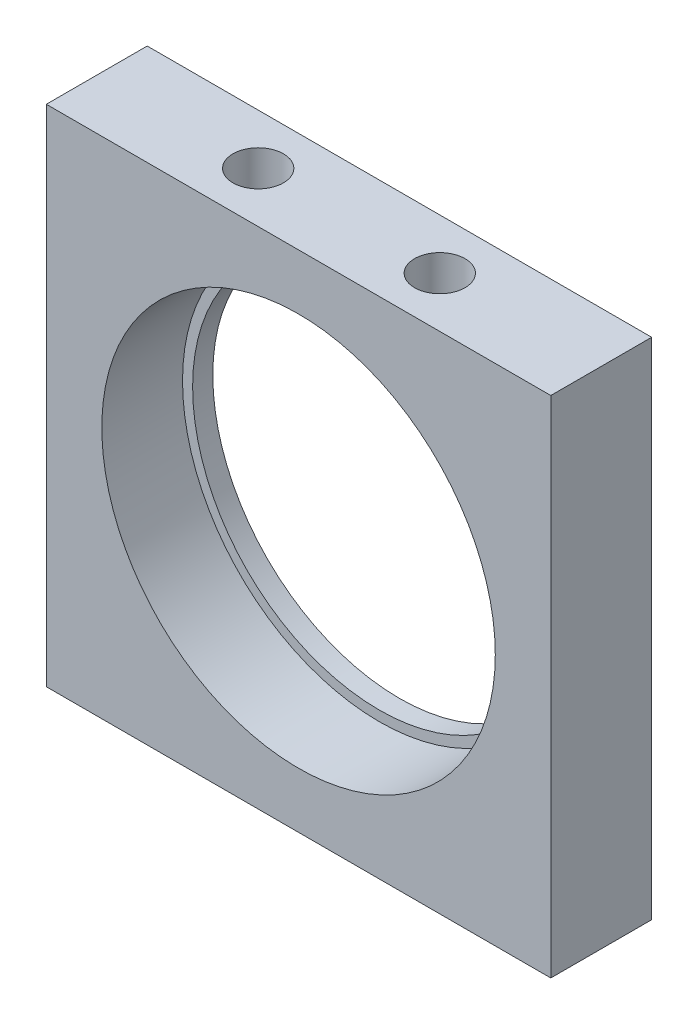
SolidWorks part; units mm, degrees
material "1060 Alloy"
ref_plane "Front Plane" through (0, 0, 0) normal (0, 0, 1) x (1, 0, 0)
ref_plane "Top Plane" through (0, 0, 0) normal (0, 1, 0) x (1, 0, 0)
ref_plane "Right Plane" through (0, 0, 0) normal (1, 0, 0) x (0, 0, -1)
sketch "Sketch1" plane through (0, 0, 0) normal (0, 0, 1) x (1, 0, 0)
  line L1 (12.5, 12.5) -> (-12.5, 12.5)
  line L2 (12.5, 12.5) -> (12.5, -12.5)
  line L3 (12.5, -12.5) -> (-12.5, -12.5)
  line L4 (-12.5, 12.5) -> (-12.5, -12.5)
  line L5 (12.5, 12.5) -> (-12.5, -12.5) construction
  line L6 (12.5, -12.5) -> (-12.5, 12.5) construction
  circle A0 centre (0, 0) radius 9.25
  point P0 (0, 0)
  dimension "D2" = 18.5
  dimension "D1" = 25
extrude "Boss-Extrude1" add sketch "Sketch1" along normal blind 5
hole_wizard "M3x0.5 Tapped Hole1" positions "Sketch3" profile "Sketch2" tap size "M3x0.5" standard "Ansi Metric"
sketch "Sketch3" plane through (0, 12.5, 0) normal (0, 1, 0) x (-1, 0, 0)
  line L0 (12.5, 2.5) -> (-12.5, 2.5) construction
  line L1 (12.5, 5) -> (12.5, 0) construction
  line L2 (-12.5, 5) -> (-12.5, 0) construction
  point P0 (4.5, 2.5)
  point P2 (-4.5, 2.5)
  dimension "D1" = 8
  dimension "D2" = 8
sketch "Sketch2" plane through (-4.5, 12.5, 2.5) normal (1, 0, 0) x (0, 0, 1)
  line L0 (0, 0) -> (0, 8.2511)
  line L1 (0, 8.2511) -> (1.25, 7.5)
  line L2 (1.25, 7.5) -> (1.25, 0)
  line L5 (1.25, 0) -> (0, 0)
  line L10 (0, 8.2511) -> (-1.25, 7.5) construction
  line L11 (0, -6.35) -> (0, 107.95) construction
  dimension "Tap Drill Dia." = 2.5
  dimension "Tap Drill Depth" = 7.5
  dimension "Drill Angle" = 118
cosmetic thread "Hole Thread1" parameters "D1"=4.626, "D2"=3
cosmetic thread "Hole Thread2" parameters "D1"=4.626, "D2"=3
sketch "Sketch4" plane through (0, 0, 5) normal (0, 0, 1) x (1, 0, 0)
  circle A0 centre (0, 0) radius 9.75
  dimension "D1" = 19.5
extrude "Cut-Extrude1" cut sketch "Sketch4" against normal offset from surface (4 mm away) 1 up to face at (0, 0, 0)
